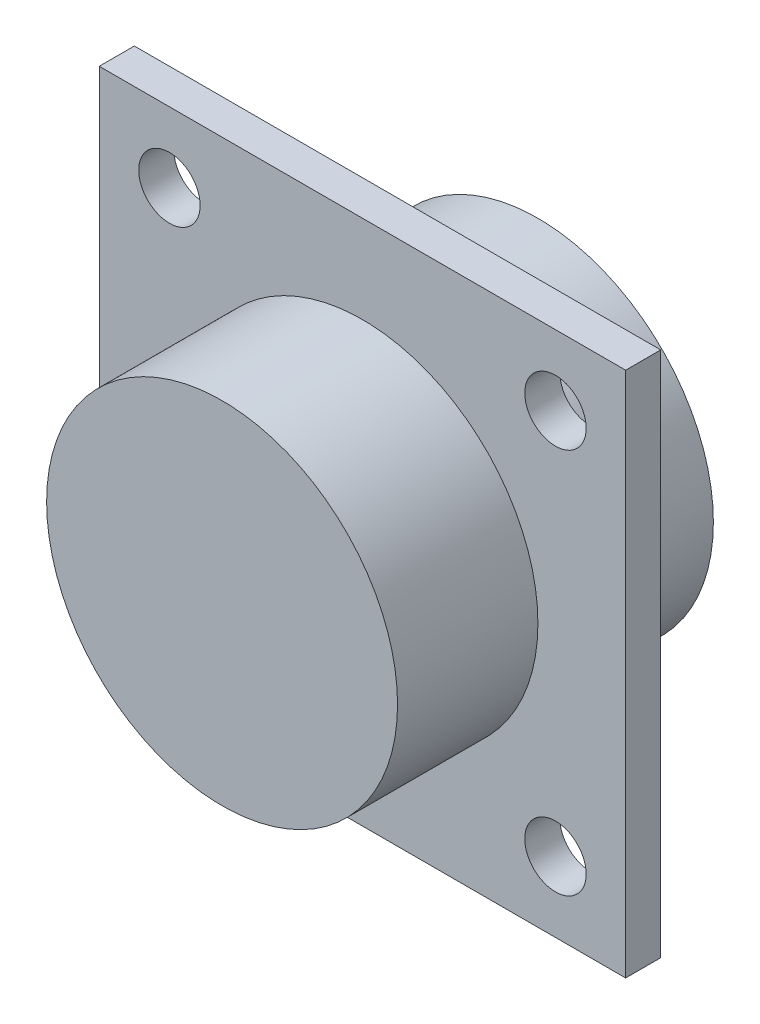
SolidWorks part; units mm, degrees
ref_plane "前视基准面" through (0, 0, 0) normal (0, 0, 1) x (1, 0, 0)
ref_plane "上视基准面" through (0, 0, 0) normal (0, 1, 0) x (1, 0, 0)
ref_plane "右视基准面" through (0, 0, 0) normal (1, 0, 0) x (0, 0, -1)
sketch "草图1" plane through (0, 0, 0) normal (0, 0, 1) x (1, 0, 0)
  line L0 (-52.2043, 0) -> (41.6414, 0) construction
  line L1 (-15, 15) -> (15, 15)
  line L2 (-15, 15) -> (-15, -15)
  line L3 (-15, -15) -> (15, -15)
  line L4 (15, 15) -> (15, -15)
  line L5 (0, -37.7561) -> (0, 33.7269) construction
  dimension "D1" = 30
  dimension "D2" = 30
extrude "凸台-拉伸1" add sketch "草图1" along normal blind 2
sketch "草图2" plane through (0, 0, 2) normal (0, 0, 1) x (1, 0, 0)
  circle A0 centre (0, 0) radius 10
  dimension "D1" = 20
extrude "凸台-拉伸2" add sketch "草图2" along normal blind 8 and the other way blind 10
sketch "草图3" plane through (0, 0, -8) normal (0, 0, -1) x (-1, 0, 0)
  circle A0 centre (0, 0) radius 8.5
  dimension "D1" = 17
extrude "切除-拉伸1" cut sketch "草图3" against normal blind 8
sketch "草图4" plane through (0, 0, 0) normal (0, 0, -1) x (-1, 0, 0)
  line L0 (-19.8882, 0) -> (19.7363, 0) construction
  line L1 (0, 19.301) -> (0, -19.6418) construction
  circle A0 centre (-11, 11) radius 1.75
  circle A1 centre (11, 11) radius 1.75
  circle A2 centre (11, -11) radius 1.75
  circle A3 centre (-11, -11) radius 1.75
  dimension "D1" = 3.5
  dimension "D2" = 22
  dimension "D3" = 22
extrude "切除-拉伸2" cut sketch "草图4" against normal blind 8
